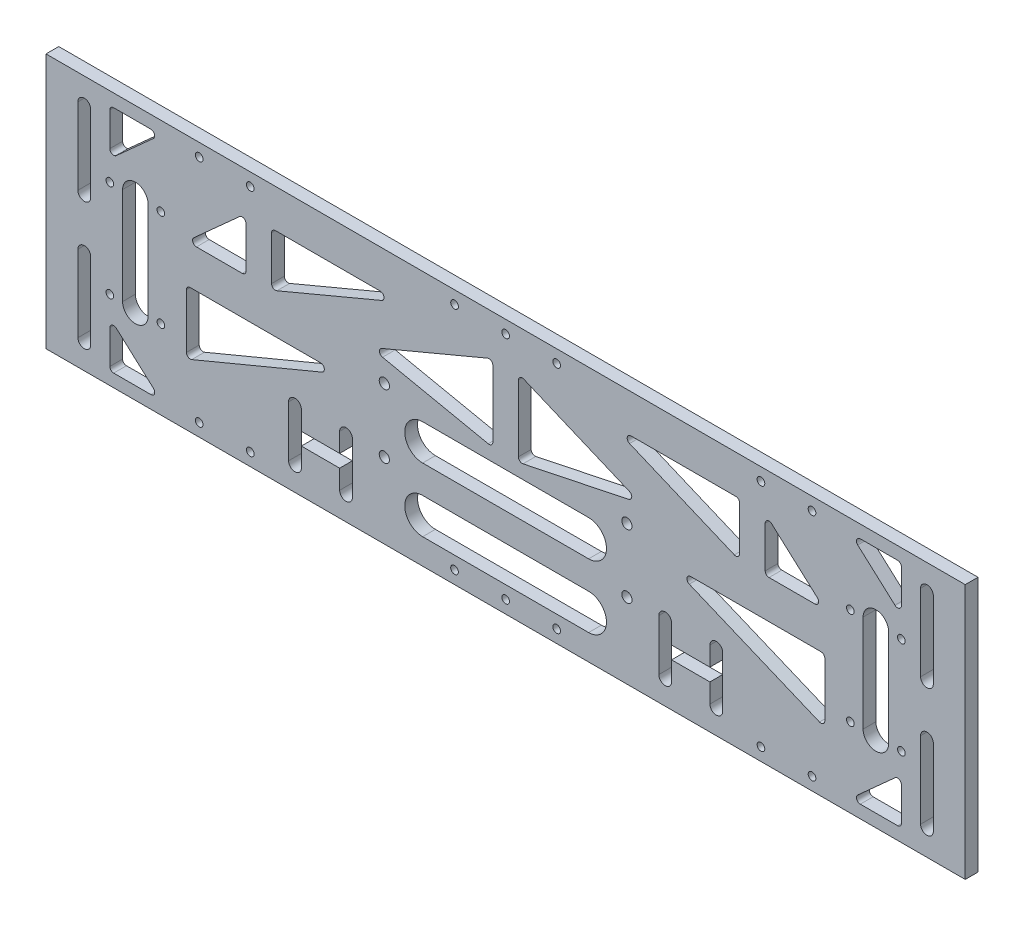
SolidWorks part; units mm, degrees
material "A-玻璃纤维"
ref_plane "前视基准面" through (0, 0, 0) normal (0, 0, 1) x (1, 0, 0)
ref_plane "上视基准面" through (0, 0, 0) normal (0, 1, 0) x (1, 0, 0)
ref_plane "右视基准面" through (0, 0, 0) normal (1, 0, 0) x (0, 0, -1)
sketch "草图1" plane through (0, 0, 0) normal (0, 0, 1) x (1, 0, 0)
  line L1 (0, 0) -> (320, 0)
  line L2 (0, 0) -> (0, 121)
  line L3 (0, 121) -> (320, 121)
  line L4 (320, 0) -> (320, 121)
  dimension "D1" = 320
  dimension "D2" = 121
extrude "凸台-拉伸1" add sketch "草图1" along normal blind 5
sketch "草图2" plane through (0, 0, 5) normal (0, 0, 1) x (1, 0, 0)
  line L0 (160, 121) -> (160, 0) construction
  line L1 (320, 121) -> (0, 121) construction
  line L2 (0, 0) -> (320, 0) construction
  line L3 (0, 121) -> (0, 0) construction
  line L4 (30, 0) -> (35, 0)
  line L5 (30, 0) -> (30, 30)
  line L6 (30, 30) -> (35, 30)
  line L7 (35, 0) -> (35, 30)
  line L8 (285, 0) -> (285, 30)
  line L9 (290, 30) -> (285, 30)
  line L10 (290, 0) -> (290, 30)
  line L11 (290, 0) -> (285, 0)
  dimension "D1" = 30
  dimension "D2" = 30
  dimension "D3" = 5
extrude "切除-拉伸1" cut sketch "草图2" against normal through all
sketch "草图3" plane through (0, 0, 5) normal (0, 0, 1) x (1, 0, 0)
  line L0 (40, 116) -> (60, 116) construction
  line L1 (160, 121) -> (160, 0) construction
  line L2 (320, 121) -> (0, 121) construction
  line L3 (35, 0) -> (285, 0) construction
  line L4 (140, 116) -> (160, 116) construction
  line L5 (0, 121) -> (0, 0) construction
  line L6 (280, 116) -> (260, 116) construction
  circle A0 centre (40, 116) radius 1.5
  circle A1 centre (60, 116) radius 1.5
  circle A2 centre (140, 116) radius 1.5
  circle A3 centre (160, 116) radius 1.5
  circle A4 centre (260, 116) radius 1.5
  circle A5 centre (280, 116) radius 1.5
  circle A6 centre (180, 116) radius 1.5
  point P22 (0, 0)
  dimension "D5" = 3
  dimension "D1" = 40
  dimension "D2" = 5
  dimension "D3" = 20
  dimension "D4" = 20
extrude "切除-拉伸2" cut sketch "草图3" against normal through all
sketch "草图4" plane through (0, 0, 5) normal (0, 0, 1) x (1, 0, 0)
  line L0 (160, 121) -> (160, 0) construction
  line L1 (5, 90) -> (25, 90) construction
  line L2 (5, 90) -> (5, 10) construction
  line L3 (5, 10) -> (25, 10) construction
  line L4 (25, 90) -> (25, 10) construction
  line L5 (320, 121) -> (0, 121) construction
  line L6 (35, 0) -> (285, 0) construction
  line L7 (0, 0) -> (30, 0) construction
  line L8 (0, 121) -> (0, 0) construction
  line L10 (295, 90) -> (295, 10) construction
  line L11 (315, 10) -> (295, 10) construction
  line L12 (315, 90) -> (315, 10) construction
  line L13 (315, 90) -> (295, 90) construction
  circle A0 centre (5, 90) radius 1.5
  circle A1 centre (25, 90) radius 1.5
  circle A2 centre (5, 10) radius 1.5
  circle A3 centre (25, 10) radius 1.5
  circle A4 centre (295, 10) radius 1.5
  circle A5 centre (315, 10) radius 1.5
  circle A6 centre (295, 90) radius 1.5
  circle A7 centre (315, 90) radius 1.5
  dimension "D5" = 3
  dimension "D1" = 10
  dimension "D2" = 80
  dimension "D3" = 5
  dimension "D4" = 20
extrude "切除-拉伸3" cut sketch "草图4" against normal through all
sketch "草图6" plane through (0, 0, 5) normal (0, 0, 1) x (1, 0, 0)
  line L0 (160, 121) -> (160, 0) construction
  line L1 (320, 121) -> (0, 121) construction
  line L2 (35, 0) -> (285, 0) construction
  line L3 (127.5, 63) -> (192.5, 63) construction
  line L4 (112.5, 50.5) -> (207.5, 50.5) construction
  line L5 (112.5, 50.5) -> (112.5, 75.5) construction
  line L6 (112.5, 75.5) -> (207.5, 75.5) construction
  line L7 (207.5, 50.5) -> (207.5, 75.5) construction
  line L8 (112.5, 50.5) -> (207.5, 75.5) construction
  line L9 (112.5, 75.5) -> (207.5, 50.5) construction
  line L10 (127.5, 70) -> (192.5, 70)
  line L11 (127.5, 56) -> (192.5, 56)
  circle A0 centre (112.5, 75.5) radius 2
  circle A1 centre (207.5, 75.5) radius 2
  circle A2 centre (207.5, 50.5) radius 2
  circle A3 centre (112.5, 50.5) radius 2
  arc A4 (127.5, 70) -> (127.5, 56) centre (127.5, 63) ccw
  arc A5 (192.5, 56) -> (192.5, 70) centre (192.5, 63) ccw
  point P6 (160, 63)
  point P17 (160, 63)
  dimension "D1" = 4
  dimension "D5" = 7
  dimension "D2" = 25
  dimension "D3" = 95
  dimension "D4" = 45.5
  dimension "D6" = 15
extrude "切除-拉伸5" cut sketch "草图6" against normal through all
sketch "草图5" plane through (0, 0, 5) normal (0, 0, 1) x (1, 0, 0)
  line L0 (5, 101.368) -> (5, 114.5)
  line L1 (6.5, 116) -> (21.0911, 116)
  line L2 (22.0945, 113.3851) -> (7.5034, 100.2531)
  line L6 (5, 90) -> (25, 90) construction
  line L7 (0, 121) -> (0, 0) construction
  line L8 (320, 121) -> (0, 121) construction
  line L9 (38.9089, 85) -> (56.8333, 85)
  line L10 (58.3333, 86.5) -> (58.3333, 102.632)
  line L11 (55.8299, 103.7469) -> (37.9055, 87.6149)
  line L12 (160, 121) -> (160, 0) construction
  line L13 (35, 0) -> (285, 0) construction
  line L14 (35, 68.5) -> (35, 47.25)
  line L15 (35, 0) -> (285, 0)
  line L16 (35, 0) -> (35, 30)
  line L17 (35, 30) -> (285, 30)
  line L18 (285, 0) -> (285, 30)
  line L19 (37.0769, 45.8654) -> (88.0769, 67.1154)
  line L20 (87.5, 70) -> (36.5, 70)
  line L24 (68.3333, 87.2569) -> (68.3333, 104.5)
  line L25 (69.8333, 106) -> (110.8883, 106)
  line L26 (111.4691, 103.117) -> (70.4142, 85.874)
  line L27 (111.7889, 84.0154) -> (153.1936, 75.3769)
  line L28 (155, 76.8453) -> (155, 102.8738)
  line L29 (152.9192, 104.2567) -> (111.5144, 86.8668)
  line L30 (315, 90) -> (295, 90) construction
  line L31 (167.0808, 104.2567) -> (208.4856, 86.8668)
  line L32 (165, 76.8453) -> (165, 102.8738)
  line L33 (208.2111, 84.0154) -> (166.8064, 75.3769)
  line L34 (208.5309, 103.117) -> (249.5858, 85.874)
  line L35 (250.1667, 106) -> (209.1117, 106)
  line L36 (251.6667, 87.2569) -> (251.6667, 104.5)
  line L40 (232.5, 70) -> (283.5, 70)
  line L41 (282.9231, 45.8654) -> (231.9231, 67.1154)
  line L42 (285, 68.5) -> (285, 47.25)
  line L43 (264.1701, 103.7469) -> (282.0945, 87.6149)
  line L44 (261.6667, 86.5) -> (261.6667, 102.632)
  line L45 (281.0911, 85) -> (263.1667, 85)
  line L46 (297.9055, 113.3851) -> (312.4966, 100.2531)
  line L47 (313.5, 116) -> (298.9089, 116)
  line L48 (315, 101.368) -> (315, 114.5)
  line L52 (192.5, 70) -> (127.5, 70) construction
  arc A2 (155, 102.8738) -> (152.9192, 104.2567) centre (153.5, 102.8738) ccw
  arc A4 (21.0911, 116) -> (22.0945, 113.3851) centre (21.0911, 114.5) cw
  arc A5 (5, 101.368) -> (7.5034, 100.2531) centre (6.5, 101.368) ccw
  arc A6 (5, 114.5) -> (6.5, 116) centre (6.5, 114.5) cw
  arc A7 (56.8333, 85) -> (58.3333, 86.5) centre (56.8333, 86.5) ccw
  arc A8 (38.9089, 85) -> (37.9055, 87.6149) centre (38.9089, 86.5) cw
  arc A9 (58.3333, 102.632) -> (55.8299, 103.7469) centre (56.8333, 102.632) ccw
  arc A10 (88.0769, 67.1154) -> (87.5, 70) centre (87.5, 68.5) ccw
  arc A11 (35, 47.25) -> (37.0769, 45.8654) centre (36.5, 47.25) ccw
  arc A12 (35, 68.5) -> (36.5, 70) centre (36.5, 68.5) cw
  arc A17 (153.1936, 75.3769) -> (155, 76.8453) centre (153.5, 76.8453) ccw
  arc A18 (111.7889, 84.0154) -> (111.5144, 86.8668) centre (112.0953, 85.4838) cw
  arc A19 (68.3333, 87.2569) -> (70.4142, 85.874) centre (69.8333, 87.2569) ccw
  arc A20 (68.3333, 104.5) -> (69.8333, 106) centre (69.8333, 104.5) cw
  arc A21 (110.8883, 106) -> (111.4691, 103.117) centre (110.8883, 104.5) cw
  arc A22 (209.1117, 106) -> (208.5309, 103.117) centre (209.1117, 104.5) ccw
  arc A23 (251.6667, 104.5) -> (250.1667, 106) centre (250.1667, 104.5) ccw
  arc A24 (251.6667, 87.2569) -> (249.5858, 85.874) centre (250.1667, 87.2569) cw
  arc A25 (208.2111, 84.0154) -> (208.4856, 86.8668) centre (207.9047, 85.4838) ccw
  arc A26 (166.8064, 75.3769) -> (165, 76.8453) centre (166.5, 76.8453) cw
  arc A30 (285, 68.5) -> (283.5, 70) centre (283.5, 68.5) ccw
  arc A31 (285, 47.25) -> (282.9231, 45.8654) centre (283.5, 47.25) cw
  arc A32 (231.9231, 67.1154) -> (232.5, 70) centre (232.5, 68.5) cw
  arc A33 (261.6667, 102.632) -> (264.1701, 103.7469) centre (263.1667, 102.632) cw
  arc A34 (281.0911, 85) -> (282.0945, 87.6149) centre (281.0911, 86.5) ccw
  arc A35 (263.1667, 85) -> (261.6667, 86.5) centre (263.1667, 86.5) cw
  arc A36 (315, 114.5) -> (313.5, 116) centre (313.5, 114.5) ccw
  arc A37 (315, 101.368) -> (312.4966, 100.2531) centre (313.5, 101.368) cw
  arc A38 (298.9089, 116) -> (297.9055, 113.3851) centre (298.9089, 114.5) ccw
  arc A39 (165, 102.8738) -> (167.0808, 104.2567) centre (166.5, 102.8738) cw
  point P23 (25, 116)
  point P26 (5, 98)
  point P29 (5, 116)
  point P40 (35, 85)
  point P43 (58.3333, 106)
  point P56 (95, 70)
  point P59 (35, 45)
  point P62 (35, 70)
  point P84 (155, 105.1307)
  point P87 (155, 75)
  point P90 (107.0698, 85)
  point P93 (68.3333, 85)
  point P96 (68.3333, 106)
  point P99 (118.3333, 106)
  point P156 (201.6667, 106)
  point P157 (251.6667, 106)
  point P158 (251.6667, 85)
  point P159 (212.9302, 85)
  point P160 (165, 75)
  point P161 (165, 105.1307)
  point P162 (285, 70)
  point P163 (285, 45)
  point P164 (225, 70)
  point P165 (261.6667, 106)
  point P166 (285, 85)
  point P167 (315, 116)
  point P168 (315, 98)
  point P169 (295, 116)
  point P186 (20, 15)
  point P189 (8, 15)
  point P192 (20, 25)
  point P202 (300, 25)
  point P203 (312, 15)
  point P204 (300, 15)
  dimension "D8" = 1.5
  dimension "D12" = 1.5
  dimension "D16" = 1.5
  dimension "D27" = 1.5
  dimension "D4" = 5
  dimension "D5" = 5
  dimension "D6" = 20
  dimension "D7" = 18
  dimension "D9" = 5
  dimension "D10" = 10
  dimension "D11" = 10
  dimension "D13" = 15
  dimension "D14" = 15
  dimension "D15" = 60
  dimension "D21" = 15
  dimension "D22" = 10
  dimension "D23" = 50
  dimension "D24" = 15
  dimension "D25" = 10
  dimension "D26" = 5
  dimension "D29" = 8
  dimension "D31" = 10
extrude "切除-拉伸4" cut sketch "草图5" against normal through all
sketch "草图7" plane through (0, 0, 0) normal (0, 0, -1) x (-1, 0, 0)
  line L0 (-290, 0) -> (-290, 30)
  line L1 (-290, 30) -> (-30, 30)
  line L2 (-30, 30) -> (-30, 0)
  line L3 (-30, 0) -> (-290, 0)
extrude "凸台-拉伸2" add sketch "草图7" against normal blind 5
sketch "草图8" plane through (0, 0, 0) normal (0, 0, -1) x (-1, 0, 0)
  line L0 (-320, 0) -> (-320, 21)
  line L1 (-320, 0) -> (-320, 121) construction
  line L2 (-320, 21) -> (0, 21)
  line L3 (0, 121) -> (0, 0) construction
  line L4 (0, 21) -> (0, 0)
  line L5 (0, 0) -> (-320, 0)
extrude "切除-拉伸6" cut sketch "草图8" against normal blind 5
sketch "草图9" plane through (0, 0, 0) normal (0, 0, -1) x (-1, 0, 0)
  line L0 (-160, 21) -> (-335, 21)
  line L1 (0, 21) -> (-320, 21) construction
  line L2 (-335, 21) -> (-335, 121)
  line L3 (-335, 121) -> (15, 121)
  line L4 (15, 121) -> (15, 21)
  line L5 (15, 21) -> (-160, 21)
  line L6 (0, 21) -> (0, 121)
  line L7 (-320, 21) -> (-320, 121)
extrude "凸台-拉伸3" add sketch "草图9" against normal blind 5 contours L0 L7 L3 L2 | L6 L5 L4 L3
sketch "草图10" plane through (0, 0, 0) normal (0, 0, -1) x (-1, 0, 0)
  line L0 (-335, 71) -> (-325, 71)
  line L1 (-335, 21) -> (-335, 121) construction
  line L2 (-325, 71) -> (-325, 121)
  line L3 (-335, 121) -> (15, 121) construction
  line L4 (-325, 71) -> (-325, 21)
  line L5 (15, 21) -> (-335, 21) construction
  line L6 (15, 71) -> (5, 71)
  line L7 (15, 121) -> (15, 21) construction
  line L8 (5, 71) -> (5, 121)
  line L9 (5, 71) -> (5, 21)
  line L10 (-325, 71) -> (-325, 81)
  line L11 (-325, 81) -> (-325, 111)
  line L12 (-325, 71) -> (-325, 61)
  line L13 (-325, 61) -> (-325, 31)
  line L14 (-325, 81) -> (-325, 111) construction
  line L15 (-327.5, 81) -> (-327.5, 111)
  line L16 (-322.5, 81) -> (-322.5, 111)
  line L17 (-325, 61) -> (-325, 31) construction
  line L18 (-322.5, 61) -> (-322.5, 31)
  line L19 (-327.5, 61) -> (-327.5, 31)
  line L20 (-160, 21) -> (-160, 121)
  line L21 (5, 61) -> (5, 31) construction
  line L22 (2.5, 61) -> (2.5, 31)
  line L23 (7.5, 61) -> (7.5, 31)
  line L24 (5, 81) -> (5, 111) construction
  line L25 (7.5, 81) -> (7.5, 111)
  line L26 (2.5, 81) -> (2.5, 111)
  arc A0 (-327.5, 81) -> (-322.5, 81) centre (-325, 81) ccw
  arc A1 (-322.5, 111) -> (-327.5, 111) centre (-325, 111) ccw
  arc A2 (-322.5, 61) -> (-327.5, 61) centre (-325, 61) ccw
  arc A3 (-327.5, 31) -> (-322.5, 31) centre (-325, 31) ccw
  arc A4 (2.5, 61) -> (7.5, 61) centre (5, 61) cw
  arc A5 (7.5, 31) -> (2.5, 31) centre (5, 31) cw
  arc A6 (7.5, 81) -> (2.5, 81) centre (5, 81) cw
  arc A7 (2.5, 111) -> (7.5, 111) centre (5, 111) cw
  point P20 (-325, 96)
  point P25 (-325, 46)
  point P34 (5, 46)
  point P41 (5, 96)
  dimension "D1" = 10
  dimension "D2" = 10
  dimension "D3" = 30
  dimension "D4" = 10
  dimension "D5" = 30
extrude "切除-拉伸7" cut sketch "草图10" against normal blind 5 contours L16 A1 L2 L10 A0 | L2 A1 L15 A0 L10 | L4 A3 L18 A2 L12 | L19 A3 L4 L12 A2 | A7 L8 A6 L25 | A7 L26 A6 L8 | A5 L23 A4 L9 | A5 L9 A4 L22
sketch "草图13" plane through (0, 0, 0) normal (0, 0, -1) x (-1, 0, 0)
  line L12 (-192.5, 63) -> (-192.5, 38)
  line L13 (-127.5, 63) -> (-127.5, 38)
  line L14 (-192.5, 38) -> (-127.5, 38) construction
  line L15 (-192.5, 45) -> (-127.5, 45)
  line L16 (-192.5, 31) -> (-127.5, 31)
  line L18 (-305, 63.5) -> (-305, 83.5)
  line L19 (-305, 63.5) -> (-305, 48.5)
  line L23 (-160, 21) -> (-160, 121)
  line L24 (15, 21) -> (-335, 21) construction
  line L25 (-335, 121) -> (15, 121) construction
  arc A1 (-192.5, 45) -> (-192.5, 31) centre (-192.5, 38) ccw
  arc A2 (-127.5, 31) -> (-127.5, 45) centre (-127.5, 38) ccw
  point P16 (-160, 38)
  dimension "D1" = 25
  dimension "D3" = 15
  dimension "D2" = 25
  dimension "D4" = 20
extrude "切除-拉伸8" cut sketch "草图13" against normal blind 5
sketch "草图15" plane through (0, 0, 0) normal (0, 0, -1) x (-1, 0, 0)
  line L0 (-313.5, 116) -> (-298.9089, 116)
  line L1 (-297.9055, 113.3851) -> (-312.4966, 100.2531)
  line L2 (-315, 114.5) -> (-315, 101.368)
  line L3 (-21.0911, 116) -> (-6.5, 116)
  line L4 (-5, 114.5) -> (-5, 101.368)
  line L5 (-7.5034, 100.2531) -> (-22.0945, 113.3851)
  line L6 (-335, 71) -> (15, 71)
  line L7 (-335, 21) -> (-335, 121) construction
  line L8 (15, 121) -> (15, 21) construction
  line L9 (-21.0911, 26) -> (-6.5, 26)
  line L10 (-5, 27.5) -> (-5, 40.632)
  line L11 (-7.5034, 41.7469) -> (-22.0945, 28.6149)
  line L12 (-315, 27.5) -> (-315, 40.632)
  line L13 (-313.5, 26) -> (-298.9089, 26)
  line L14 (-297.9055, 28.6149) -> (-312.4966, 41.7469)
  circle A0 centre (-280, 116) radius 1.5
  circle A1 centre (-260, 116) radius 1.5
  circle A2 centre (-180, 116) radius 1.5
  circle A3 centre (-160, 116) radius 1.5
  circle A4 centre (-140, 116) radius 1.5
  circle A5 centre (-60, 116) radius 1.5
  circle A6 centre (-40, 116) radius 1.5
  circle A7 centre (-25, 90) radius 1.5
  circle A8 centre (-5, 90) radius 1.5
  circle A9 centre (-315, 90) radius 1.5
  circle A10 centre (-295, 90) radius 1.5
  arc A11 (-315, 101.368) -> (-312.4966, 100.2531) centre (-313.5, 101.368) ccw
  arc A12 (-313.5, 116) -> (-315, 114.5) centre (-313.5, 114.5) ccw
  arc A13 (-297.9055, 113.3851) -> (-298.9089, 116) centre (-298.9089, 114.5) ccw
  arc A14 (-21.0911, 116) -> (-22.0945, 113.3851) centre (-21.0911, 114.5) ccw
  arc A15 (-5, 114.5) -> (-6.5, 116) centre (-6.5, 114.5) ccw
  arc A16 (-7.5034, 100.2531) -> (-5, 101.368) centre (-6.5, 101.368) ccw
  circle A17 centre (-25, 52) radius 1.5
  circle A18 centre (-5, 52) radius 1.5
  arc A19 (-5, 27.5) -> (-6.5, 26) centre (-6.5, 27.5) cw
  arc A20 (-7.5034, 41.7469) -> (-5, 40.632) centre (-6.5, 40.632) cw
  arc A21 (-21.0911, 26) -> (-22.0945, 28.6149) centre (-21.0911, 27.5) cw
  circle A22 centre (-40, 26) radius 1.5
  circle A23 centre (-60, 26) radius 1.5
  circle A24 centre (-140, 26) radius 1.5
  circle A25 centre (-160, 26) radius 1.5
  circle A26 centre (-180, 26) radius 1.5
  circle A27 centre (-260, 26) radius 1.5
  circle A28 centre (-280, 26) radius 1.5
  arc A29 (-313.5, 26) -> (-315, 27.5) centre (-313.5, 27.5) cw
  arc A30 (-297.9055, 28.6149) -> (-298.9089, 26) centre (-298.9089, 27.5) cw
  arc A31 (-315, 40.632) -> (-312.4966, 41.7469) centre (-313.5, 40.632) cw
  circle A32 centre (-295, 52) radius 1.5
  circle A33 centre (-315, 52) radius 1.5
extrude "切除-拉伸9" cut sketch "草图15" against normal through all contours A33 | A31 L12 A29 L13 A30 L14 | A32 | A28 | A27 | A26 | A25 | A24 | A23 | A22 | A21 L9 A19 L10 A20 L11 | A18 | A17
sketch "草图16" plane through (0, 0, 0) normal (0, 0, -1) x (-1, 0, 0)
  line L0 (-335, 71) -> (15, 71)
  line L1 (-335, 21) -> (-335, 121) construction
  line L2 (15, 121) -> (15, 21) construction
  line L3 (-315, 90) -> (-295, 90)
  line L4 (-315, 52) -> (-295, 52)
  line L5 (-305, 52) -> (-305, 90)
  line L6 (-305, 52) -> (-305, 90) construction
  line L7 (-310, 52) -> (-310, 90)
  line L8 (-300, 52) -> (-300, 90)
  line L9 (-160, 21) -> (-160, 121)
  line L10 (15, 21) -> (-335, 21) construction
  line L11 (-335, 121) -> (15, 121) construction
  line L12 (-15, 52) -> (-15, 90) construction
  line L13 (-10, 52) -> (-10, 90)
  line L14 (-20, 52) -> (-20, 90)
  arc A0 (-310, 52) -> (-300, 52) centre (-305, 52) ccw
  arc A1 (-300, 90) -> (-310, 90) centre (-305, 90) ccw
  arc A2 (-10, 52) -> (-20, 52) centre (-15, 52) cw
  arc A3 (-20, 90) -> (-10, 90) centre (-15, 90) cw
  point P16 (-305, 71)
  point P29 (-15, 71)
extrude "切除-拉伸10" cut sketch "草图16" against normal through all contours L4 L8 L0 L5 | L4 A0 | L7 L4 L5 L0 | L0 L8 L3 L5 | L7 L0 L5 L3 | L3 A1 | A2 L13 L0 L14 | A3 L14 L0 L13
sketch "草图17" plane through (0, 0, 0) normal (0, 0, -1) x (-1, 0, 0)
  line L0 (-207.5, 50.5) -> (-257.5, 50.5)
  line L1 (-257.5, 50.5) -> (-257.5, 30.5)
  line L2 (-257.5, 30.5) -> (-207.5, 30.5)
  line L3 (-207.5, 30.5) -> (-207.5, 50.5)
  line L4 (-207.5, 40.5) -> (-257.5, 40.5)
  line L5 (-257.5, 50.5) -> (-247.5, 50.5)
  line L6 (-247.5, 50.5) -> (-247.5, 30.5)
  line L7 (-207.5, 50.5) -> (-217.5, 50.5)
  line L8 (-217.5, 50.5) -> (-217.5, 30.5)
  line L9 (-247.5, 50.5) -> (-242.5, 50.5)
  line L10 (-242.5, 50.5) -> (-242.5, 30.5)
  line L11 (-217.5, 50.5) -> (-222.5, 50.5)
  line L12 (-222.5, 50.5) -> (-222.5, 30.5)
  line L13 (-242.5, 50.5) -> (-242.5, 30.5) construction
  line L14 (-240, 50.5) -> (-240, 30.5)
  line L15 (-245, 50.5) -> (-245, 30.5)
  line L16 (-222.5, 50.5) -> (-222.5, 30.5) construction
  line L17 (-220, 50.5) -> (-220, 30.5)
  line L18 (-225, 50.5) -> (-225, 30.5)
  line L19 (-242.5, 40.5) -> (-222.5, 40.5) construction
  line L20 (-242.5, 43) -> (-222.5, 43)
  line L21 (-242.5, 38) -> (-222.5, 38)
  line L22 (-160, 21) -> (-160, 121)
  line L23 (15, 21) -> (-335, 21) construction
  line L24 (-335, 121) -> (15, 121) construction
  line L25 (-97.5, 50.5) -> (-97.5, 30.5) construction
  line L26 (-100, 50.5) -> (-100, 30.5)
  line L27 (-95, 50.5) -> (-95, 30.5)
  line L28 (-77.5, 40.5) -> (-97.5, 40.5) construction
  line L29 (-77.5, 43) -> (-97.5, 43)
  line L30 (-77.5, 38) -> (-97.5, 38)
  line L31 (-77.5, 50.5) -> (-77.5, 30.5) construction
  line L32 (-80, 50.5) -> (-80, 30.5)
  line L33 (-75, 50.5) -> (-75, 30.5)
  arc A0 (-240, 50.5) -> (-245, 50.5) centre (-242.5, 50.5) ccw
  arc A1 (-245, 30.5) -> (-240, 30.5) centre (-242.5, 30.5) ccw
  arc A2 (-220, 50.5) -> (-225, 50.5) centre (-222.5, 50.5) ccw
  arc A3 (-225, 30.5) -> (-220, 30.5) centre (-222.5, 30.5) ccw
  arc A4 (-242.5, 43) -> (-242.5, 38) centre (-242.5, 40.5) ccw
  arc A5 (-222.5, 38) -> (-222.5, 43) centre (-222.5, 40.5) ccw
  arc A6 (-100, 50.5) -> (-95, 50.5) centre (-97.5, 50.5) cw
  arc A7 (-95, 30.5) -> (-100, 30.5) centre (-97.5, 30.5) cw
  arc A8 (-77.5, 43) -> (-77.5, 38) centre (-77.5, 40.5) cw
  arc A9 (-97.5, 38) -> (-97.5, 43) centre (-97.5, 40.5) cw
  arc A10 (-80, 50.5) -> (-75, 50.5) centre (-77.5, 50.5) cw
  arc A11 (-75, 30.5) -> (-80, 30.5) centre (-77.5, 30.5) cw
  point P11 (-242.5, 40.5)
  point P20 (-222.5, 40.5)
  point P25 (-232.5, 40.5)
  point P40 (-97.5, 40.5)
  point P47 (-87.5, 40.5)
  point P54 (-77.5, 40.5)
  dimension "D1" = 20
extrude "切除-拉伸11" cut sketch "草图17" against normal through all contours A11 L33 A8 L30 L32 | A8 L29 L32 L30 | A10 L32 L29 A8 L33 | L32 L29 L27 L30 | A9 L30 L27 L29 | L26 A9 L29 L27 A6 | L30 A9 L26 A7 L27 | L10 L20 L14 L0 | A4 L10 L0 L15 | L0 A0 | L20 L14 L4 L18 | L20 L10 L4 L14 | L10 A4 L4 | L4 A4 L10 | L10 L21 L14 L4 | L14 L21 L18 L4 | L21 L10 L2 L14 | A4 L15 L2 L10 | L2 A1 | L2 A3 | A5 L12 L2 L17 | L21 L18 L2 L12 | L18 L21 L12 L4 | L12 A5 L4 | L4 A5 L12 | L20 L18 L4 L12 | L18 L20 L12 L0 | A5 L17 L11 L12 | L11 A2 L0
sketch "草图18" plane through (0, 0, 0) normal (0, 0, -1) x (-1, 0, 0)
  line L0 (-335, 21) -> (-340, 21)
  line L1 (-340, 21) -> (-340, 121)
  line L2 (-340, 121) -> (-335, 121)
  line L3 (-335, 121) -> (-335, 21)
  line L4 (15, 21) -> (20, 21)
  line L5 (20, 21) -> (20, 121)
  line L6 (20, 121) -> (15, 121)
  line L7 (15, 121) -> (15, 21)
extrude "凸台-拉伸4" add sketch "草图18" against normal blind 5
